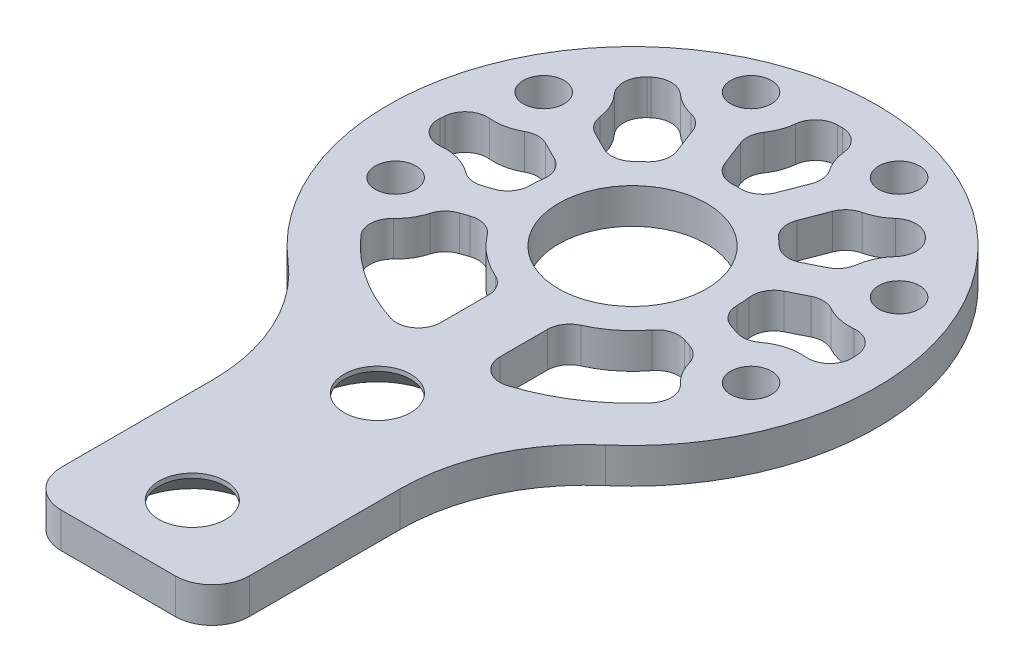
SolidWorks part; units mm, degrees
material "1060 Alloy"
ref_plane "Front Plane" through (0, 0, 0) normal (0, 0, 1) x (1, 0, 0)
ref_plane "Top Plane" through (0, 0, 0) normal (0, 1, 0) x (1, 0, 0)
ref_plane "Right Plane" through (0, 0, 0) normal (1, 0, 0) x (0, 0, -1)
sketch "Sketch1" plane through (0, 0, 0) normal (0, 1, 0) x (1, 0, 0)
  line L0 (-12.7, -69.4583) -> (12.7, -69.4583)
  line L1 (12.7, -69.4583) -> (12.7, -30.4583)
  line L2 (-12.7, -69.4583) -> (-12.7, -30.4583)
  arc A0 (12.7, -30.4583) -> (-12.7, -30.4583) centre (0, 0) ccw
  point P5 (0, -69.4583)
  dimension "D2" = 66
  dimension "D1" = 25.4
  dimension "D3" = 39
extrude "Boss-Extrude1" add sketch "Sketch1" along normal blind 4.7625 contours A0 L2 L0 L1
sketch "Sketch2" plane through (0, 0, 0) normal (0, -1, 0) x (1, 0, 0)
  line L0 (0, -55) -> (0, 55) construction
  point P0 (-10, -26)
  point P1 (-24, -12)
  point P4 (-24, 8)
  point P15 (24, 8)
  point P17 (24, -12)
  point P18 (10, -26)
  dimension "D2" = 26
  dimension "D1" = 8
  dimension "D3" = 10
  dimension "D4" = 24
  dimension "D5" = 20
sketch "Sketch5" plane through (0, 0, 0) normal (0, -1, 0) x (1, 0, 0)
  circle A0 centre (0, 0) radius 10
  dimension "D1" = 20
extrude "Cut-Extrude1" cut sketch "Sketch5" against normal through all
sketch "Sketch6" plane through (0, 0, 0) normal (0, -1, 0) x (1, 0, 0)
  line L0 (0, 69.4583) -> (0, 34.4583) construction
  line L1 (-12.7, 69.4583) -> (12.7, 69.4583) construction
  point P5 (0, 59.4583)
  dimension "D1" = 25
  dimension "D2" = 10
hole_wizard "CSK for M8 Flat Head Machine Screw1" positions "Sketch7" profile "Sketch8" countersink size "M8" standard "ANSI Metric" end condition through all
sketch "Sketch7" plane through (0, 0, 0) normal (0, -1, 0) x (-1, 0, 0)
  point P0 (0, -34.4583)
  point P3 (0, -59.4583)
sketch "Sketch8" plane through (0, 0, 34.4583) normal (1, 0, 0) x (0, 0, -1)
  line L0 (0, 0) -> (0, 4.7625)
  line L1 (0, 4.7625) -> (4.5, 4.7625)
  line L2 (4.5, 4.7625) -> (4.5, 4.15)
  line L3 (4.5, 4.15) -> (8.65, 0)
  line L5 (8.65, 0) -> (0, 0)
  line L6 (-4.5, 4.15) -> (-8.65, 0) construction
  line L11 (0, -6.35) -> (0, 107.95) construction
  dimension "Thru Hole Dia." = 9
  dimension "Thru Hole Depth" = 4.7625
  dimension "Near C'Sink Dia." = 17.3
  dimension "Near C'Sink Angle" = 90
fillet "Fillet1" radius 25 2 edges at (-12.7, 2.3813, 30.4583) (12.7, 2.3813, 30.4583)
hole_wizard "M5 Clearance Hole1" positions "Sketch9" profile "Sketch10" hole size "M5" standard "ANSI Metric" end condition through all
sketch "Sketch9" plane through (0, 0, 0) normal (0, -1, 0) x (-1, 0, 0)
  point P0 (10, 26)
  point P3 (24, 12)
  point P6 (24, -8)
  point P9 (-10, 26)
  point P12 (-24, 12)
  point P15 (-24, -8)
sketch "Sketch10" plane through (-10, 0, -26) normal (1, 0, 0) x (0, 0, -1)
  line L0 (0, 0) -> (0, 4.7625)
  line L1 (0, 4.7625) -> (2.75, 4.7625)
  line L2 (2.75, 4.7625) -> (2.75, 0.025)
  line L3 (2.75, 0.025) -> (2.775, 0)
  line L5 (2.775, 0) -> (0, 0)
  line L6 (-2.75, 0.025) -> (-2.775, 0) construction
  line L11 (0, -6.35) -> (0, 107.95) construction
  dimension "Thru Hole Dia." = 5.5
  dimension "Thru Hole Depth" = 4.7625
  dimension "Near C'Sink Dia." = 5.55
  dimension "Near C'Sink Angle" = 90
fillet "Fillet2" radius 5 2 edges at (-12.7, 2.3813, 69.4583) (12.7, 2.3813, 69.4583)
hole_wizard "M8 Clearance Hole1" positions "3DSketch1" profile "Sketch11" hole size "M8" standard "ANSI Metric"
sketch3d "3DSketch1"
  point P0 (0, 0, 37.6917)
  point P3 (0, 0, 62.6917)
sketch "Sketch11" plane through (0, 0, 37.6917) normal (1, 0, 0) x (0, 0, -1)
  line L0 (0, 0) -> (0, 4.7625)
  line L1 (0, 4.7625) -> (4.5, 4.7625)
  line L2 (4.5, 4.7625) -> (4.5, 0)
  line L5 (4.5, 0) -> (0, 0)
  line L11 (0, -6.35) -> (0, 107.95) construction
  dimension "Thru Hole Dia." = 9
  dimension "Thru Hole Depth" = 4.7625
sketch "Sketch12" plane through (0, 4.7625, 0) normal (0, 1, 0) x (1, 0, 0)
  line L0 (0, -28) -> (0, 0)
  line L3 (-24, -8) -> (0, 0)
  line L6 (-24, 12) -> (0, 0)
  line L9 (-10, 26) -> (0, 0)
  line L12 (0, 0) -> (10, 26)
  line L14 (0, 0) -> (24, 12)
  line L15 (0, 0) -> (24, -8)
  line L17 (-12.3334, 25.1026) -> (-2.3334, -0.8974)
  line L18 (-25.118, 9.7639) -> (-1.118, -2.2361)
  line L19 (-23.2094, -10.3717) -> (0.7906, -2.3717)
  line L20 (2.3334, -0.8974) -> (12.3334, 25.1026)
  line L21 (1.118, -2.2361) -> (25.118, 9.7639)
  line L22 (-0.7906, -2.3717) -> (23.2094, -10.3717)
  line L23 (-7.6666, 26.8974) -> (2.3334, 0.8974)
  line L24 (-22.882, 14.2361) -> (1.118, 2.2361)
  line L25 (-24.7906, -5.6283) -> (-0.7906, 2.3717)
  line L26 (-2.3334, 0.8974) -> (7.6666, 26.8974)
  line L27 (-1.118, 2.2361) -> (22.882, 14.2361)
  line L28 (0.7906, 2.3717) -> (24.7906, -5.6283)
  line L29 (4, -28) -> (4, 0)
  line L30 (-4, -28) -> (-4, 0)
  circle A16 centre (0, -34.4583) radius 9
  circle A17 centre (0, 0) radius 28
  arc A18 (21.45, -25.0778) -> (-21.45, -25.0778) centre (0, 0) ccw construction
  circle A19 centre (-24, -8) radius 6.75
  circle A20 centre (-24, 12) radius 6.75
  circle A21 centre (-10, 26) radius 6.75
  circle A22 centre (10, 26) radius 6.75
  circle A23 centre (24, 12) radius 6.75
  circle A24 centre (24, -8) radius 6.75
  circle A25 centre (0, -59.4583) radius 9
  circle A26 centre (0, 0) radius 14
  circle A27 centre (0, 0) radius 10 construction
  arc A30 (-21.687, -14.3413) -> (21.687, -14.3413) centre (0, 0) ccw
  circle A31 centre (-24, -8) radius 2.75 construction
  circle M25 centre (0, 0) radius 10
  dimension "D2" = 4
  dimension "D1" = 5
  dimension "D3" = 2.5
  dimension "D7" = 18
  dimension "D8" = 4
  dimension "D10" = 2
  dimension "D4" = 2.5
  dimension "D5" = 4
  dimension "D6" = 4
extrude "Cut-Extrude2" cut sketch "Sketch12" against normal blind 10 contours A20 A17 A19 L25 L18 M25 | A24 A17 A23 L21 L28 M25 | A21 A17 A20 L24 L17 M25 | A23 A17 A22 L20 L27 M25 | A22 A17 A21 L23 L26 M25 | A19 A30 L30 A26 L19 | L29 A30 A24 L22 A26
fillet "Fillet3" radius 3 40 edges at (-7.2783, 2.3813, -11.9594) (-21.2925, 2.3813, -18.1832) (-27.3221, 2.3813, -6.1241) (-16.0266, 2.3813, -22.9597) (-3.4894, 2.3813, -27.7817) (-10.0826, 2.3813, -19.2505) (-17.2739, 2.3813, -11.4321) (-5.4158, 2.3813, -21.0454) (-2.6116, 2.3813, -13.7543) (-11.2027, 2.3813, -8.3964) (-19.51, 2.3813, -6.9599) (-27.8897, 2.3813, 2.4834) (-18.8424, 2.3813, 3.6456) (-13.4387, 2.3813, -3.9243) (-13.8587, 2.3813, 1.9843) (-4, 2.3813, 13.4164) (-12.2775, 2.3813, 6.7277) (-17.2612, 2.3813, 8.389) (16.0266, 2.3813, -22.9597) (3.4894, 2.3813, -27.7817) (5.4158, 2.3813, -21.0454) (2.6116, 2.3813, -13.7543) (7.2783, 2.3813, -11.9594) (10.0826, 2.3813, -19.2505) (27.3221, 2.3813, -6.1241) (21.2925, 2.3813, -18.1832) (17.2739, 2.3813, -11.4321) (11.2027, 2.3813, -8.3964) (13.4387, 2.3813, -3.9243) (19.51, 2.3813, -6.9599) (27.8897, 2.3813, 2.4834) (18.8424, 2.3813, 3.6456) (13.8587, 2.3813, 1.9843) (17.2612, 2.3813, 8.389) (12.2775, 2.3813, 6.7277) (4, 2.3813, 13.4164) (21.687, 2.3813, 14.3413) (4, 2.3813, 25.6905) (-4, 2.3813, 25.6905) (-21.687, 2.3813, 14.3413)
